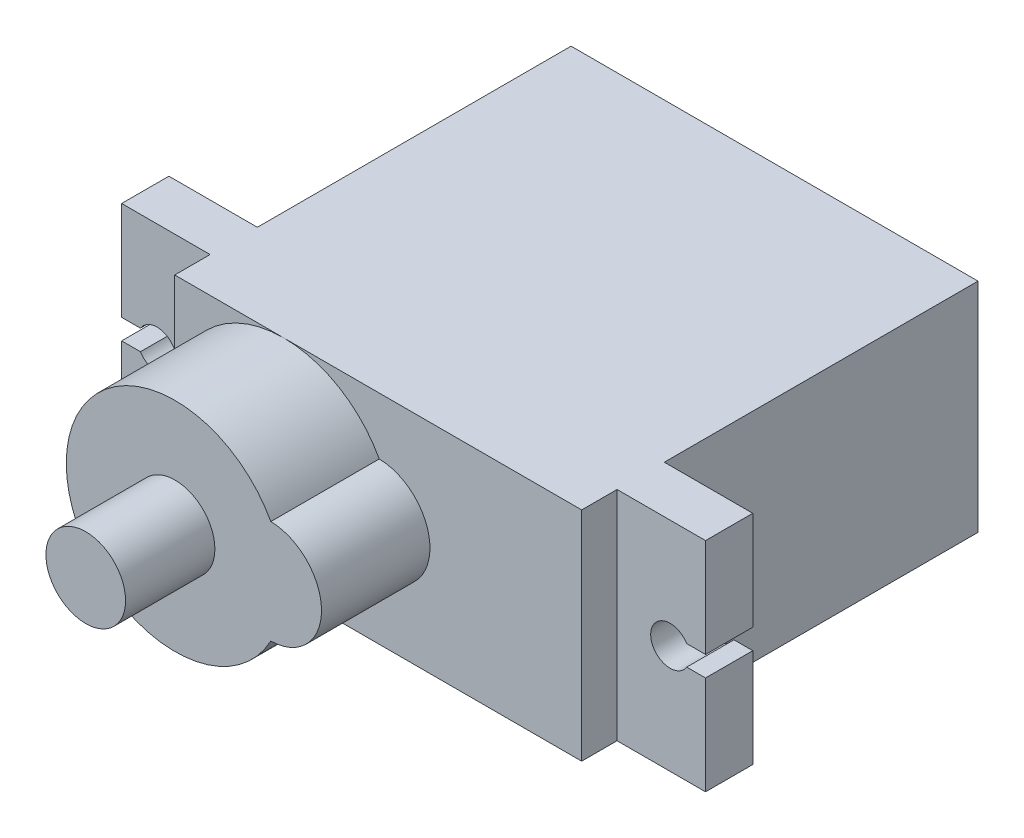
SolidWorks part; units mm, degrees
ref_plane "Front Plane" through (0, 0, 0) normal (0, 0, 1) x (1, 0, 0)
ref_plane "Top Plane" through (0, 0, 0) normal (0, 1, 0) x (1, 0, 0)
ref_plane "Right Plane" through (0, 0, 0) normal (1, 0, 0) x (0, 0, -1)
sketch "Sketch2" plane through (0, 0, 0) normal (0, 0, 1) x (1, 0, 0)
  line L1 (-11.5, 6.15) -> (11.5, 6.15)
  line L2 (-11.5, 6.15) -> (-11.5, -6.15)
  line L3 (-11.5, -6.15) -> (11.5, -6.15)
  line L4 (11.5, 6.15) -> (11.5, -6.15)
  line L5 (-11.5, 6.15) -> (11.5, -6.15) construction
  line L6 (-11.5, -6.15) -> (11.5, 6.15) construction
  point P0 (0, 0)
  dimension "D1" = 23
  dimension "D2" = 12.3
extrude "Boss-Extrude1" add sketch "Sketch2" along normal blind 22.4
sketch "Sketch3" plane through (11.5, 0, 0) normal (1, 0, 0) x (0, 0, -1)
  line L0 (-22.4, 6.15) -> (0, 6.15) construction
  line L1 (-20.4, 6.15) -> (-17.73, 6.15)
  line L2 (-20.4, 6.15) -> (-20.4, -6.15)
  line L3 (-20.4, -6.15) -> (-17.73, -6.15)
  line L4 (-17.73, 6.15) -> (-17.73, -6.15)
  line L5 (-22.4, -6.15) -> (0, -6.15) construction
  line L6 (-22.4, -6.15) -> (-22.4, 6.15) construction
  dimension "D1" = 2.67
  dimension "D2" = 2
extrude "Boss-Extrude2" add sketch "Sketch3" along normal blind 5
sketch "Sketch6" plane through (0, 0, 20.4) normal (0, 0, 1) x (1, 0, 0)
  line L0 (16.5, 6.15) -> (16.5, -6.15) construction
  line L1 (15.4377, 0.575) -> (16.5, 0.575)
  line L2 (15.4377, -0.575) -> (16.5, -0.575)
  line L3 (16.5, -0.575) -> (16.5, 0.575)
  arc A0 (15.4377, 0.575) -> (15.4377, -0.575) centre (14.5, 0) ccw
  point P9 (16.5, 0)
  dimension "D1" = 2.2
  dimension "D2" = 2
  dimension "D3" = 1.15
extrude "Cut-Extrude1" cut sketch "Sketch6" against normal through all
mirror "Mirror1" about plane through (0, 0, 0) normal (1, 0, 0) of "Cut-Extrude1", "Boss-Extrude2"
sketch "Sketch4" plane through (0, 0, 22.4) normal (0, 0, 1) x (1, 0, 0)
  line L0 (11.5, 6.15) -> (-11.5, 6.15) construction
  line L1 (-11.5, 6.15) -> (-11.5, -6.15) construction
  line L2 (-11.5, -6.15) -> (11.5, -6.15) construction
  arc A0 (0.0602, 2.9244) -> (0.0602, -2.9244) centre (-5.35, 0) ccw
  arc A1 (0.0602, -2.9244) -> (0.0602, 2.9244) centre (0, 0) ccw
  dimension "D1" = 5.85
extrude "Boss-Extrude3" add sketch "Sketch4" along normal blind 6.13
sketch "Sketch5" plane through (0, 0, 28.53) normal (0, 0, 1) x (1, 0, 0)
  circle A0 centre (-5.35, 0) radius 2.25
  arc A1 (0.0602, 2.9244) -> (0.0602, -2.9244) centre (-5.35, 0) ccw construction
  dimension "D1" = 4.5
extrude "Boss-Extrude4" add sketch "Sketch5" along normal blind 5.05
